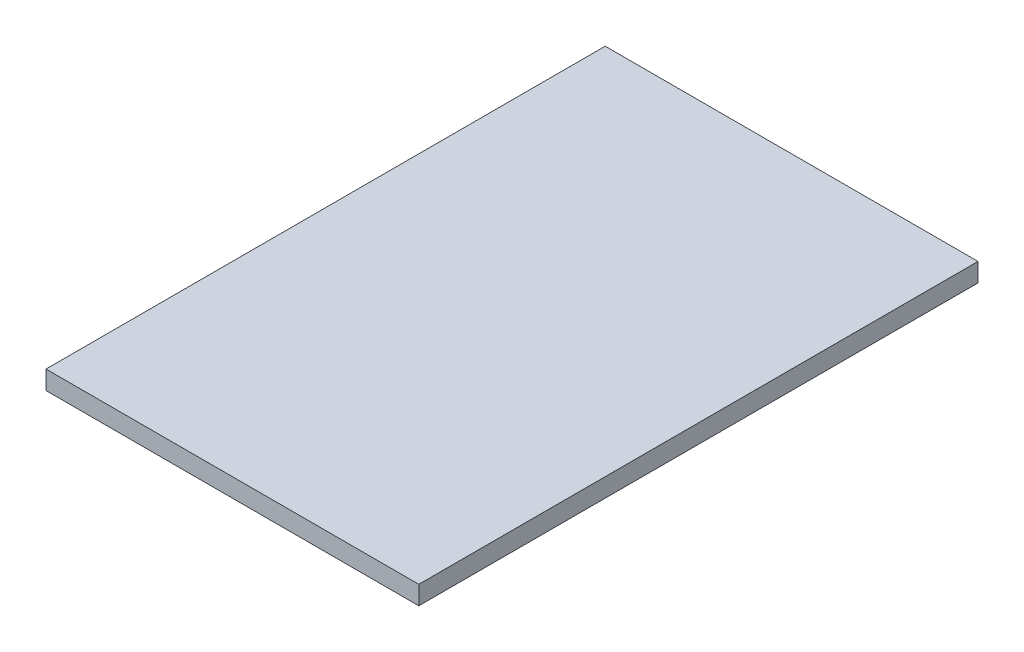
SolidWorks part; units mm, degrees
ref_plane "Płaszczyzna przednia" through (0, 0, 0) normal (0, 0, 1) x (1, 0, 0)
ref_plane "Płaszczyzna górna" through (0, 0, 0) normal (0, 1, 0) x (1, 0, 0)
ref_plane "Płaszczyzna prawa" through (0, 0, 0) normal (1, 0, 0) x (0, 0, -1)
sketch "Szkic1" plane through (0, 0, 0) normal (0, 1, 0) x (1, 0, 0)
  line L1 (-100, -150) -> (100, -150)
  line L2 (-100, -150) -> (-100, 150)
  line L3 (-100, 150) -> (100, 150)
  line L4 (100, -150) -> (100, 150)
  line L5 (-100, -150) -> (100, 150) construction
  line L6 (-100, 150) -> (100, -150) construction
  point P0 (0, 0)
  dimension "D1" = 200
  dimension "D2" = 300
extrude "Dodanie-wyciągnięcie1" add sketch "Szkic1" along normal blind 10
